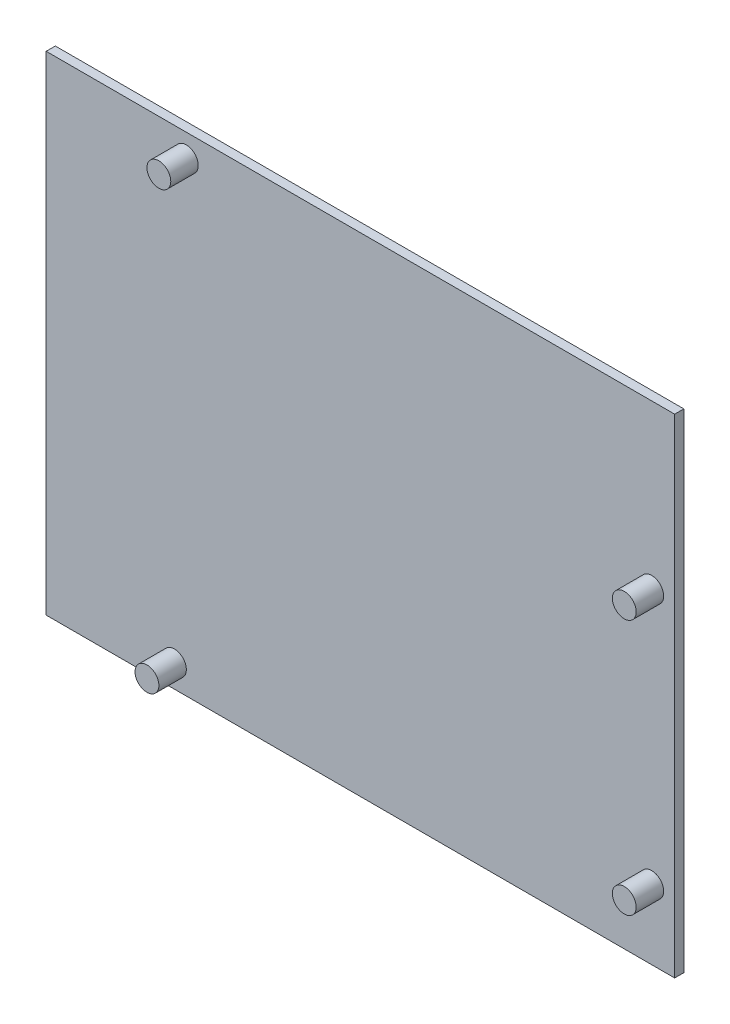
SolidWorks part; units mm, degrees
ref_plane "Front Plane" through (0, 0, 0) normal (0, 0, 1) x (1, 0, 0)
ref_plane "Top Plane" through (0, 0, 0) normal (0, 1, 0) x (1, 0, 0)
ref_plane "Right Plane" through (0, 0, 0) normal (1, 0, 0) x (0, 0, -1)
sketch "Sketch1" plane through (0, 0, 0) normal (0, 0, 1) x (1, 0, 0)
  line L1 (0, 0) -> (68.6, 0)
  line L2 (0, 0) -> (0, 53.3)
  line L3 (0, 53.3) -> (68.6, 53.3)
  line L4 (68.6, 0) -> (68.6, 53.3)
  dimension "D1" = 68.6
  dimension "D2" = 53.3
extrude "Boss-Extrude1" add sketch "Sketch1" along normal blind 1
sketch "Sketch2" plane through (0, 0, 1) normal (0, 0, 1) x (1, 0, 0)
  circle A0 centre (14, 2.5) radius 1.3
  circle A1 centre (15.3, 50.8) radius 1.3
  circle A2 centre (66.1, 7.6) radius 1.3
  circle A3 centre (66.1, 35.5) radius 1.3
extrude "Boss-Extrude4" add sketch "Sketch2" along normal blind 3
